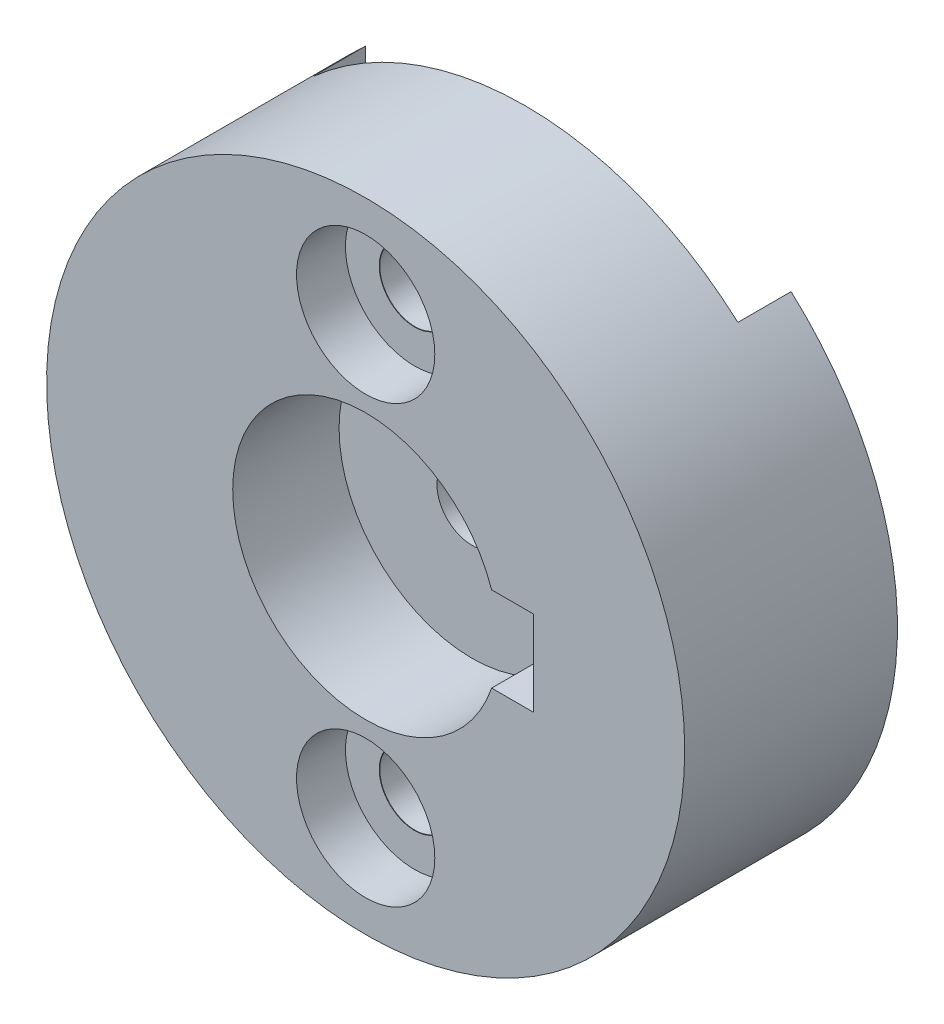
SolidWorks part; units mm, degrees
ref_plane "Plan de face" through (0, 0, 0) normal (0, 0, 1) x (1, 0, 0)
ref_plane "Plan de dessus" through (0, 0, 0) normal (0, 1, 0) x (1, 0, 0)
ref_plane "Plan de droite" through (0, 0, 0) normal (1, 0, 0) x (0, 0, -1)
sketch "Esquisse1" plane through (0, 0, 0) normal (0, 0, 1) x (1, 0, 0)
  circle A0 centre (0, 0) radius 30
  dimension "D1" = 60
extrude "Boss.-Extru.1" add sketch "Esquisse1" along normal blind 20
sketch "Esquisse2" plane through (0, 0, 0) normal (0, 0, -1) x (-1, 0, 0)
  line L1 (-20, -39.3168) -> (20, -39.3168)
  line L2 (-20, -39.3168) -> (-20, 39.3168)
  line L3 (-20, 39.3168) -> (20, 39.3168)
  line L4 (20, -39.3168) -> (20, 39.3168)
  line L5 (-20, -39.3168) -> (20, 39.3168) construction
  line L6 (-20, 39.3168) -> (20, -39.3168) construction
  point P0 (0, 0)
  dimension "D1" = 40
extrude "Enlèv. mat.-Extru.1" cut sketch "Esquisse2" against normal blind 5
sketch "Esquisse3" plane through (0, 0, 20) normal (0, 0, 1) x (1, 0, 0)
  circle A0 centre (0, 0) radius 12.5
  dimension "D1" = 25
extrude "Enlèv. mat.-Extru.2" cut sketch "Esquisse3" against normal blind 10
hole_wizard "Dégagement M61" positions "Esquisse6" profile "Esquisse5" hole size "M6" standard "JIS" end condition through all
sketch "Esquisse6" plane through (0, 0, 10) normal (0, 0, 1) x (1, 0, 0)
  point P0 (0, 0)
sketch "Esquisse5" plane through (0, 0, 10) normal (1, 0, 0) x (0, -1, 0)
  line L0 (0, 0) -> (0, 10)
  line L1 (0, 10) -> (3.3, 10)
  line L2 (3.3, 10) -> (3.3, 0)
  line L5 (3.3, 0) -> (0, 0)
  line L11 (0, -6.35) -> (0, 107.95) construction
  dimension "Diamètre du perçage jusqu'au prochain" = 6.6
  dimension "Profondeur du perçage jusqu'au prochain" = 10
hole_wizard "Chambrage pour vis à tête ronde bombée M41" positions "Esquisse8" profile "Esquisse7" counterbore size "M4" standard "Ansi Metric" end condition through all
sketch "Esquisse8" plane through (0, 0, 5) normal (0, 0, -1) x (-1, 0, 0)
  point P0 (0, 0)
sketch "Esquisse7" plane through (0, 0, 5) normal (1, 0, 0) x (0, 1, 0)
  line L0 (0, 0) -> (0, 15)
  line L1 (0, 15) -> (2.25, 15)
  line L2 (2.25, 3.125) -> (2.25, 15)
  line L3 (2.25, 3.125) -> (2.275, 3.1)
  line L4 (2.275, 3.1) -> (4.5, 3.1)
  line L5 (4.5, 3.1) -> (4.5, 0)
  line L7 (0, 0) -> (4.5, 0)
  line L9 (-2.25, 3.125) -> (-2.275, 3.1) construction
  line L11 (0, -6.35) -> (0, 107.95) construction
  dimension "Diamètre du perçage jusqu'au prochain" = 4.5
  dimension "Profondeur du perçage jusqu'au prochain" = 15
  dimension "Diamètre du chambrage" = 9
  dimension "Profondeur du chambrage" = 3.1
  dimension "Diamètre du fraisage milieu" = 4.55
  dimension "Angle du fraisage milieu" = 90
hole_wizard "Chambrage pour vis à tête ronde bombée M61" positions "Esquisse10" profile "Esquisse9" counterbore size "M6" standard "Ansi Metric" end condition through all
sketch "Esquisse10" plane through (0, 0, 20) normal (0, 0, 1) x (1, 0, 0)
  point P0 (0, -20.5)
  point P2 (0, 20.5)
sketch "Esquisse9" plane through (0, -20.5, 20) normal (1, 0, 0) x (0, -1, 0)
  line L0 (0, 0) -> (0, 20)
  line L1 (0, 20) -> (3.3, 20)
  line L2 (3.3, 4.625) -> (3.3, 20)
  line L3 (3.3, 4.625) -> (3.325, 4.6)
  line L4 (3.325, 4.6) -> (6.5, 4.6)
  line L5 (6.5, 4.6) -> (6.5, 0)
  line L7 (0, 0) -> (6.5, 0)
  line L9 (-3.3, 4.625) -> (-3.325, 4.6) construction
  line L11 (0, -6.35) -> (0, 107.95) construction
  dimension "Diamètre du perçage jusqu'au prochain" = 6.6
  dimension "Profondeur du perçage jusqu'au prochain" = 20
  dimension "Diamètre du chambrage" = 13
  dimension "Profondeur du chambrage" = 4.6
  dimension "Diamètre du fraisage milieu" = 6.65
  dimension "Angle du fraisage milieu" = 90
sketch "Esquisse11" plane through (0, 0, 20) normal (0, 0, 1) x (1, 0, 0)
  line L0 (9.8, 4) -> (9.8, -4)
  line L1 (9.8, 4) -> (15.8, 4)
  line L2 (9.8, -4) -> (15.8, -4)
  line L3 (15.8, 4) -> (15.8, -4)
  line L4 (0, 0) -> (43.9058, 0) construction
  dimension "D3" = 15.8
  dimension "D1" = 8
  dimension "D2" = 6
  dimension "D4" = 4
extrude "Enlèv. mat.-Extru.8" cut sketch "Esquisse11" against normal blind 10
